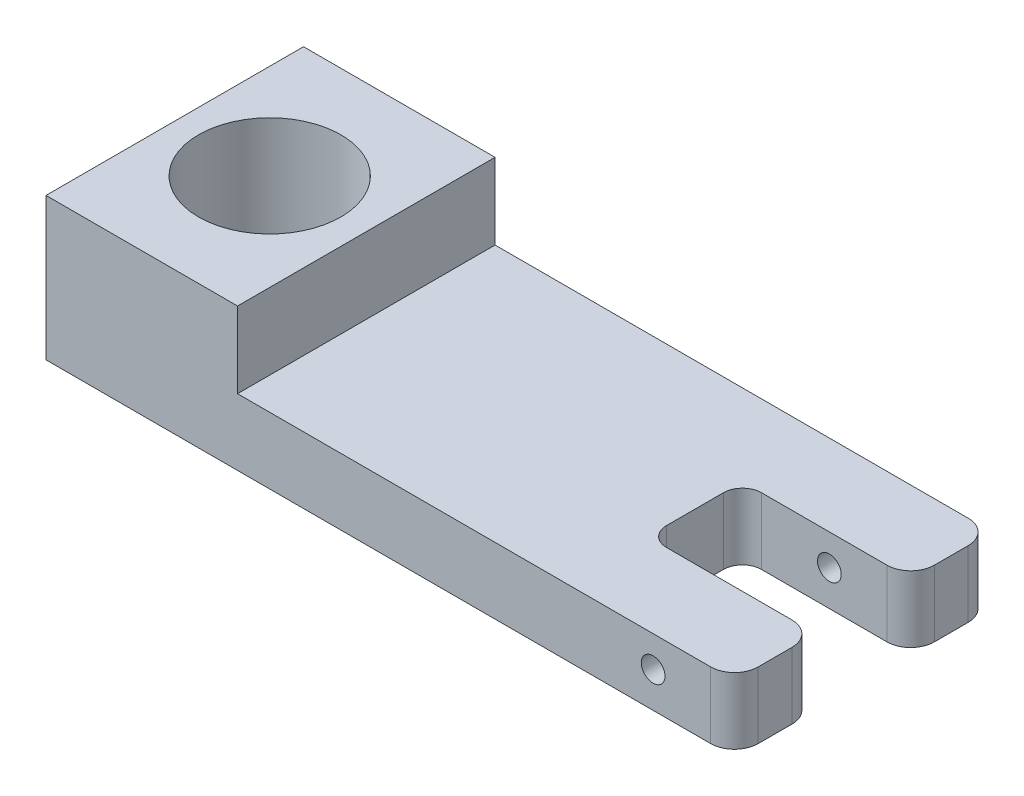
SolidWorks part; units mm, degrees
ref_plane "Спереди" through (0, 0, 0) normal (0, 0, 1) x (1, 0, 0)
ref_plane "Сверху" through (0, 0, 0) normal (0, 1, 0) x (1, 0, 0)
ref_plane "Справа" through (0, 0, 0) normal (1, 0, 0) x (0, 0, -1)
sketch "Эскиз1" plane through (0, 0, 0) normal (0, 1, 0) x (1, 0, 0)
  line L0 (-15, 0) -> (-15, 58.2175) construction
  line L1 (-20, 27.1196) -> (125, 27.1196)
  line L2 (-20, 27.1196) -> (-20, -27.1196)
  line L3 (-20, -27.1196) -> (125, -27.1196)
  line L4 (125, 27.1196) -> (125, -27.1196)
  circle A0 centre (0, 0) radius 15
  dimension "D1" = 30
  dimension "D2" = 5
extrude "Вытянуть1" add sketch "Эскиз1" along normal blind 14
sketch "Эскиз2" plane through (0, 0, 0) normal (0, 1, 0) x (1, 0, 0)
  line L1 (93.569, -10) -> (130.5426, -10)
  line L2 (93.5739, 10) -> (130.5426, 10)
  line L3 (130.5426, -10) -> (130.5426, 10)
  line L5 (89.569, -5.9984) -> (89.5739, 6.0016)
  arc A2 (89.569, -5.9984) -> (93.569, -10) centre (93.569, -6) ccw
  arc A3 (93.5739, 10) -> (89.5739, 6.0016) centre (93.5739, 6) ccw
  dimension "D3" = 4
  dimension "D4" = 130.5426
extrude "Вырез-Вытянуть1" cut sketch "Эскиз2" along normal blind 50
fillet "Скругление2" radius 5 4 edges at (125, 7, 10) (125, 7, -10) (125, 7, -27.1196) (125, 7, 27.1196)
sketch "Эскиз3" plane through (0, 0, 0) normal (0, 0, 1) x (1, 0, 0)
  circle A0 centre (107.8714, 7.4611) radius 2.5
  dimension "D1" = 5
extrude "Вырез-Вытянуть2" cut sketch "Эскиз3" against normal mid plane 72
sketch "Эскиз4" plane through (0, 14, 0) normal (0, 1, 0) x (1, 0, 0)
  line L0 (120, 27.1196) -> (-20, 27.1196) construction
  line L1 (-20, -27.1196) -> (20.3425, -27.1196)
  line L2 (-20, -27.1196) -> (-20, 27.1196)
  line L3 (-20, 27.1196) -> (20.3425, 27.1196)
  line L4 (20.3425, -27.1196) -> (20.3425, 27.1196)
  circle A0 centre (0, 0) radius 15
extrude "Вытянуть2" add sketch "Эскиз4" along normal blind 16
